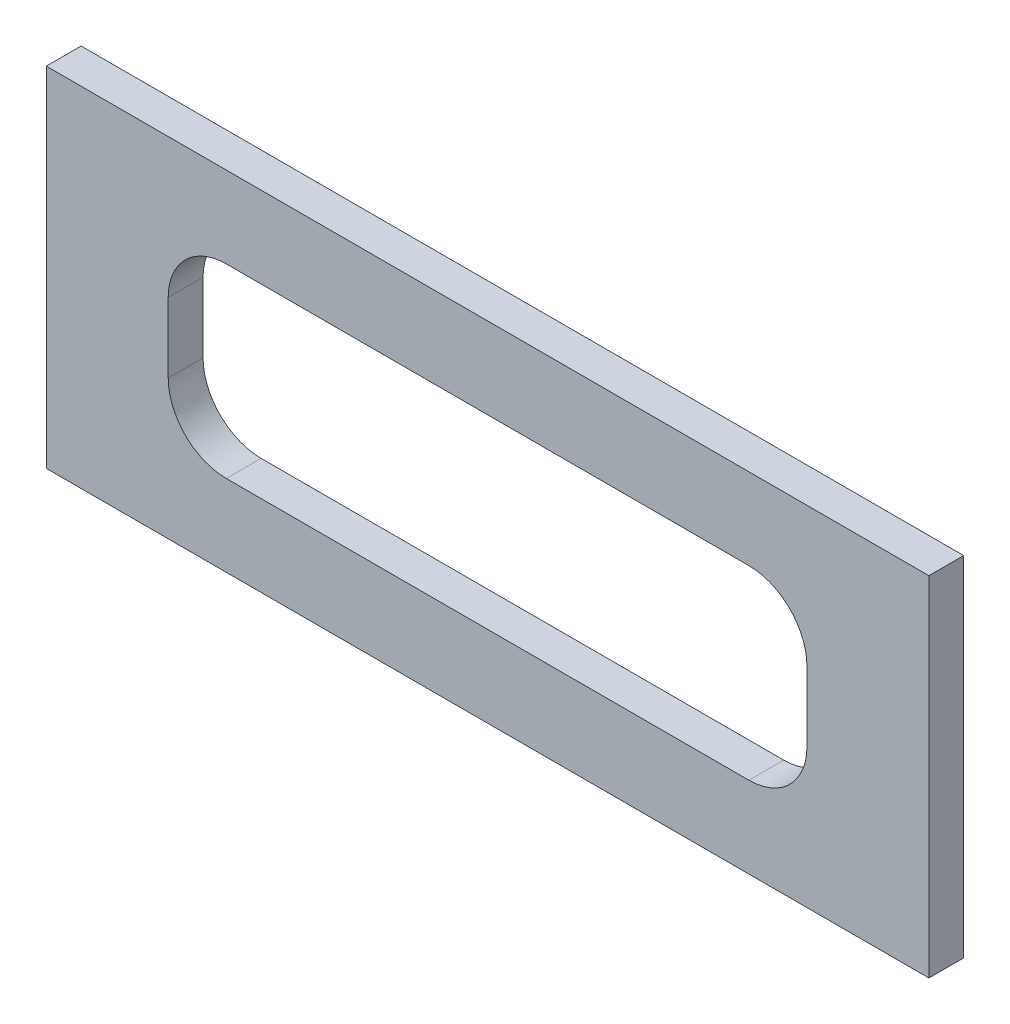
SolidWorks part; units mm, degrees
material "MDF"
ref_plane "Plano frontal" through (0, 0, 0) normal (0, 0, 1) x (1, 0, 0)
ref_plane "Plano superior" through (0, 0, 0) normal (0, 1, 0) x (1, 0, 0)
ref_plane "Plano direito" through (0, 0, 0) normal (1, 0, 0) x (0, 0, -1)
sketch "Esboço1" plane through (0, 0, 0) normal (0, 0, 1) x (1, 0, 0)
  line L0 (0, -70.6609) -> (0, 57.9855) construction
  line L1 (76, -30) -> (-76, -30)
  line L2 (76, -30) -> (76, 30)
  line L3 (76, 30) -> (-76, 30)
  line L4 (-76, -30) -> (-76, 30)
  line L5 (-85.6543, 0) -> (88.0353, 0) construction
  line L7 (45, -16) -> (-45, -16)
  line L8 (55, -6) -> (55, 6)
  line L9 (45, 16) -> (-45, 16)
  line L10 (-55, -6) -> (-55, 6)
  arc A0 (55, 6) -> (45, 16) centre (45, 6) ccw
  arc A1 (45, -16) -> (55, -6) centre (45, -6) ccw
  arc A2 (-45, -16) -> (-55, -6) centre (-45, -6) cw
  arc A3 (-45, 16) -> (-55, 6) centre (-45, 6) ccw
  point P16 (55, 16)
  point P19 (55, -16)
  point P22 (-55, -16)
  dimension "D9" = 10
  dimension "D1" = 76
  dimension "D2" = 30
  dimension "D3" = 76
  dimension "D4" = 55
  dimension "D5" = 55
  dimension "D6" = 16
  dimension "D7" = 16
  dimension "D8" = 30
extrude "Ressalto-extrusão2" add sketch "Esboço1" along normal blind 6
